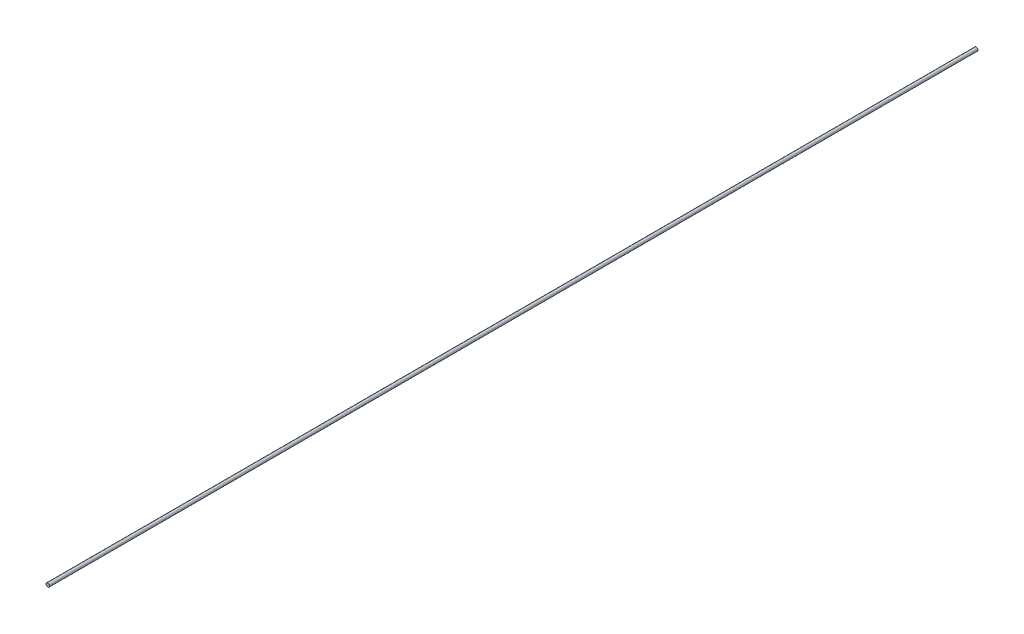
SolidWorks part; units mm, degrees
ref_plane "Front Plane" through (0, 0, 0) normal (0, 0, 1) x (1, 0, 0)
ref_plane "Top Plane" through (0, 0, 0) normal (0, 1, 0) x (1, 0, 0)
ref_plane "Right Plane" through (0, 0, 0) normal (1, 0, 0) x (0, 0, -1)
sketch "Sketch1" plane through (0, 0, 0) normal (0, 0, 1) x (1, 0, 0)
  circle A0 centre (0, 0) radius 4.75
  dimension "D1" = 9.5
extrude "Boss-Extrude1" add sketch "Sketch1" along normal mid plane 2500
